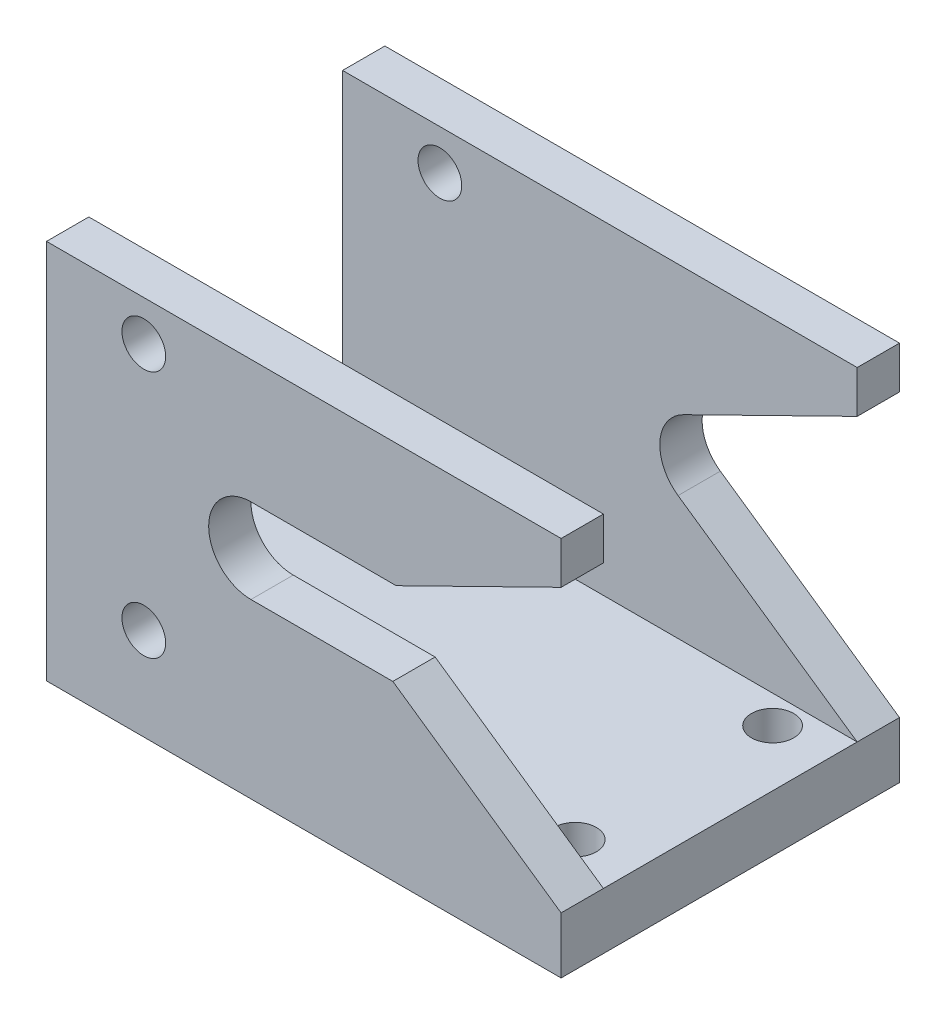
SolidWorks part; units mm, degrees
ref_plane "Front Plane" through (0, 0, 0) normal (0, 0, 1) x (1, 0, 0)
ref_plane "Top Plane" through (0, 0, 0) normal (0, 1, 0) x (1, 0, 0)
ref_plane "Right Plane" through (0, 0, 0) normal (1, 0, 0) x (0, 0, -1)
sketch "Sketch1" plane through (0, 0, 0) normal (0, 1, 0) x (1, 0, 0)
  line L1 (0, 0) -> (36.5, 0)
  line L2 (0, 0) -> (0, 24)
  line L3 (0, 24) -> (36.5, 24)
  line L4 (36.5, 0) -> (36.5, 24)
  dimension "D1" = 36.5
  dimension "D2" = 24
extrude "Boss-Extrude1" add sketch "Sketch1" along normal blind 4 contours L2 L1 L4 L3
sketch "Sketch2" plane through (0, 4, 0) normal (0, 1, 0) x (1, 0, 0)
  line L0 (0, 24) -> (0, 0) construction
  line L1 (0, 3) -> (36.5, 3)
  line L2 (0, 3) -> (0, 0)
  line L3 (0, 0) -> (36.5, 0)
  line L4 (36.5, 3) -> (36.5, 0)
  line L5 (36.5, 0) -> (36.5, 24) construction
  line L6 (36.5, 21) -> (0, 21)
  line L7 (36.5, 21) -> (36.5, 24)
  line L8 (36.5, 24) -> (0, 24)
  line L9 (0, 21) -> (0, 24)
  dimension "D1" = 3
  dimension "D2" = 3
extrude "Boss-Extrude2" add sketch "Sketch2" along normal blind 23
sketch "Sketch3" plane through (0, 0, 0) normal (0, 0, 1) x (1, 0, 0)
  line L0 (36.5, 27) -> (36.5, 0) construction
  line L1 (36.5, 27) -> (36.5, 0)
  line L2 (23.7942, 12.7821) -> (36.5, 4)
  line L3 (0, 0) -> (36.5, 0) construction
  line L4 (36.5, 23.9972) -> (24.1771, 17.9426)
  circle A0 centre (25.5, 15.25) radius 3
  circle A1 centre (6.9, 6.55) radius 1.55
  circle A2 centre (6.9, 24.15) radius 1.55
  dimension "D1" = 6
  dimension "D2" = 11
  dimension "D3" = 15.25
  dimension "D4" = 4
  dimension "D7" = 3.1
  dimension "D8" = 6.55
  dimension "D9" = 17.6
  dimension "D10" = 29.6
  dimension "D11" = 29.6
  dimension "D12" = 3.1
  dimension "D5" = 15.4455
  dimension "D6" = 13.73
extrude "Cut-Extrude2" cut sketch "Sketch3" against normal through all contours A0 | A0 L2 L1 L4 | A2 | A1
sketch "Sketch5" plane through (0, 0, 0) normal (0, 0, 1) x (1, 0, 0)
  line L0 (36.5, 27) -> (36.5, 23.9972) construction
  line L1 (0, 0) -> (36.5, 0) construction
  line L2 (14.5, 12.25) -> (24.5641, 12.25)
  line L3 (23.7942, 12.7821) -> (36.5, 4) construction
  line L4 (14.5, 18.25) -> (24.8028, 18.25)
  line L5 (36.5, 23.9972) -> (24.1771, 17.9426) construction
  circle A0 centre (14.5, 15.25) radius 3
  dimension "D1" = 22
  dimension "D2" = 6
  dimension "D3" = 15.25
extrude "Cut-Extrude3" cut sketch "Sketch5" against normal up to next
sketch "Sketch6" plane through (0, 4, 0) normal (0, 1, 0) x (1, 0, 0)
  line L0 (18.25, 24) -> (18.25, 0) construction
  line L1 (36.5, 24) -> (0, 24) construction
  line L2 (0, 0) -> (36.5, 0) construction
  line L3 (0, 12) -> (36.5, 12) construction
  line L4 (0, 21) -> (0, 3) construction
  line L5 (36.5, 3) -> (36.5, 21) construction
  circle A0 centre (4, 19) radius 1.5
  circle A1 centre (32.5, 19) radius 1.5
  circle A2 centre (32.5, 5) radius 1.5
  circle A3 centre (4, 5) radius 1.5
  dimension "D1" = 3
  dimension "D2" = 4
  dimension "D3" = 5
extrude "Cut-Extrude4" cut sketch "Sketch6" against normal through all
